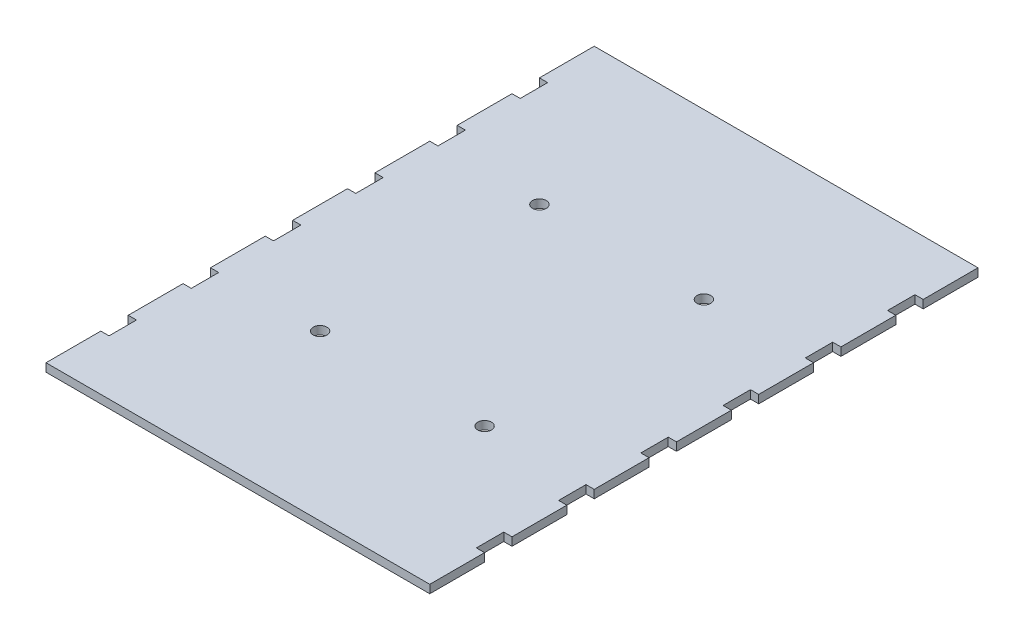
SolidWorks part; units mm, degrees
ref_plane "Front Plane" through (0, 0, 0) normal (0, 0, 1) x (1, 0, 0)
ref_plane "Top Plane" through (0, 0, 0) normal (0, 1, 0) x (1, 0, 0)
ref_plane "Right Plane" through (0, 0, 0) normal (1, 0, 0) x (0, 0, -1)
sketch "Sketch1" plane through (0, 0, 0) normal (0, 1, 0) x (1, 0, 0)
  line L1 (-70, 100) -> (70, 100)
  line L2 (-70, 100) -> (-70, -100)
  line L3 (-70, -100) -> (70, -100)
  line L4 (70, 100) -> (70, -100)
  line L5 (-70, 100) -> (70, -100) construction
  line L6 (-70, -100) -> (70, 100) construction
  point P0 (0, 0)
  dimension "D1" = 200
  dimension "D2" = 140
extrude "Boss-Extrude1" add sketch "Sketch1" along normal blind 3
sketch "Sketch2" plane through (0, 3, 0) normal (0, 1, 0) x (1, 0, 0)
  circle A0 centre (-30, 40) radius 2.5
  circle A1 centre (30, 40) radius 2.5
  circle A2 centre (-30, -40) radius 2.5
  circle A3 centre (30, -40) radius 2.5
  point P0 (0, 0)
  dimension "D3" = 5
  dimension "D1" = 80
  dimension "D2" = 60
extrude "Cut-Extrude1" cut sketch "Sketch2" against normal blind 10
sketch "Sketch3" plane through (0, 3, 0) normal (0, 1, 0) x (1, 0, 0)
  line L0 (67, -50) -> (67, -40)
  line L2 (70, -80) -> (70, -70)
  line L4 (67, -80) -> (67, -70)
  line L5 (67, -80) -> (70, -80)
  line L6 (67, -70) -> (70, -70)
  line L7 (-70, -100) -> (70, -100) construction
  line L36 (0, -100) -> (0, 100) construction
  line L37 (70, 100) -> (-70, 100) construction
  line L38 (67, -40) -> (70, -40)
  line L39 (70, -50) -> (70, -40)
  line L40 (67, -50) -> (70, -50)
  line L41 (67, -20) -> (67, -10)
  line L42 (67, -10) -> (70, -10)
  line L43 (70, -20) -> (70, -10)
  line L44 (67, -20) -> (70, -20)
  line L45 (67, 10) -> (67, 20)
  line L46 (67, 20) -> (70, 20)
  line L47 (70, 10) -> (70, 20)
  line L48 (67, 10) -> (70, 10)
  line L49 (67, 40) -> (67, 50)
  line L50 (67, 50) -> (70, 50)
  line L51 (70, 40) -> (70, 50)
  line L52 (67, 40) -> (70, 40)
  line L53 (67, 70) -> (67, 80)
  line L54 (67, 80) -> (70, 80)
  line L55 (70, 70) -> (70, 80)
  line L56 (67, 70) -> (70, 70)
  line L57 (-67, -80) -> (-70, -80)
  line L58 (-70, -80) -> (-70, -70)
  line L59 (-67, -70) -> (-70, -70)
  line L60 (-67, -80) -> (-67, -70)
  line L61 (-67, -50) -> (-70, -50)
  line L62 (-70, -50) -> (-70, -40)
  line L63 (-67, -40) -> (-70, -40)
  line L64 (-67, -50) -> (-67, -40)
  line L65 (-67, -20) -> (-70, -20)
  line L66 (-70, -20) -> (-70, -10)
  line L67 (-67, -10) -> (-70, -10)
  line L68 (-67, -20) -> (-67, -10)
  line L69 (-67, 10) -> (-70, 10)
  line L70 (-70, 10) -> (-70, 20)
  line L71 (-67, 20) -> (-70, 20)
  line L72 (-67, 10) -> (-67, 20)
  line L73 (-67, 40) -> (-70, 40)
  line L74 (-70, 40) -> (-70, 50)
  line L75 (-67, 50) -> (-70, 50)
  line L76 (-67, 40) -> (-67, 50)
  line L77 (-67, 70) -> (-70, 70)
  line L78 (-70, 70) -> (-70, 80)
  line L79 (-67, 80) -> (-70, 80)
  line L80 (-67, 70) -> (-67, 80)
  dimension "D1" = 3
  dimension "D2" = 20
  dimension "D3" = 10
  dimension "D4" = 6
extrude "Cut-Extrude2" cut sketch "Sketch3" against normal blind 10
